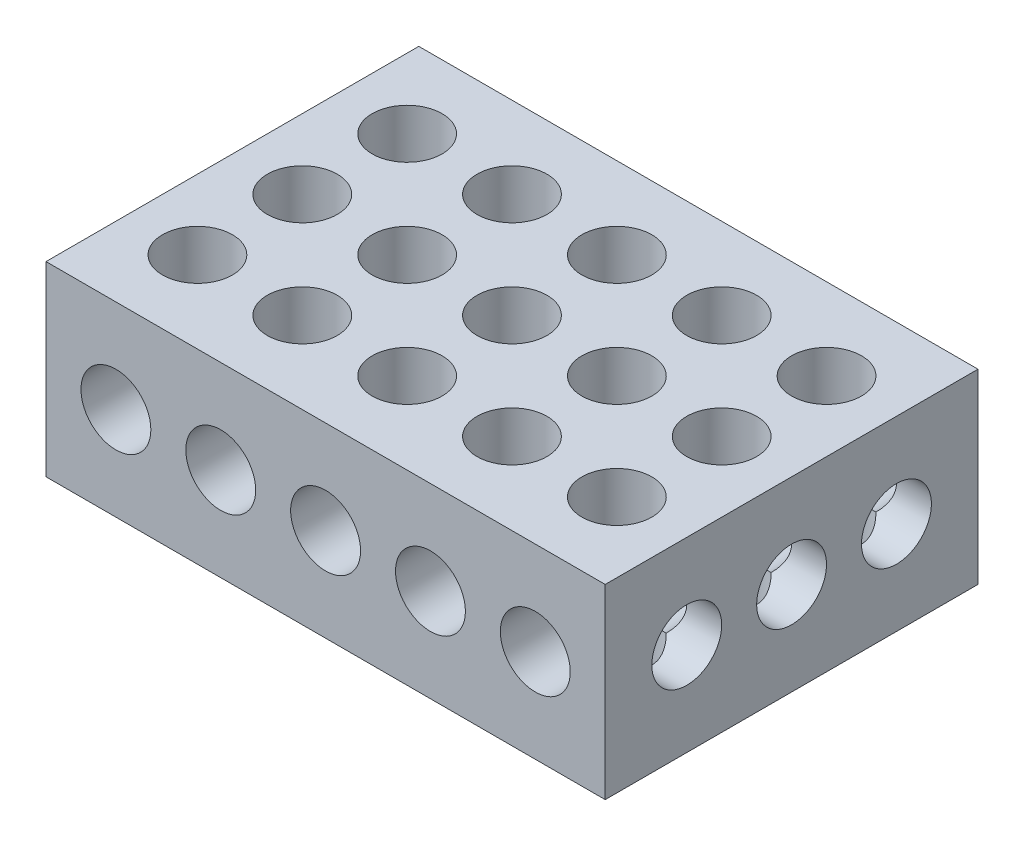
SolidWorks part; units mm, degrees
material "Plain Carbon Steel"
ref_plane "Front Plane" through (0, 0, 0) normal (0, 0, 1) x (1, 0, 0)
ref_plane "Top Plane" through (0, 0, 0) normal (0, 1, 0) x (1, 0, 0)
ref_plane "Right Plane" through (0, 0, 0) normal (1, 0, 0) x (0, 0, -1)
sketch "Sketch1" plane through (0, 0, 0) normal (0, 1, 0) x (1, 0, 0)
  line L1 (38.1, -25.4) -> (-38.1, -25.4)
  line L2 (38.1, -25.4) -> (38.1, 25.4)
  line L3 (38.1, 25.4) -> (-38.1, 25.4)
  line L4 (-38.1, -25.4) -> (-38.1, 25.4)
  line L5 (38.1, -25.4) -> (-38.1, 25.4) construction
  line L6 (38.1, 25.4) -> (-38.1, -25.4) construction
  point P0 (0, 0)
  dimension "D1" = 50.8
  dimension "D2" = 76.2
extrude "Boss-Extrude1" add sketch "Sketch1" along normal mid plane 25.4
sketch "Sketch2" plane through (0, 0, 25.4) normal (0, 0, 1) x (1, 0, 0)
  circle A0 centre (-28.575, 0) radius 4.7625
  circle A1 centre (-14.2875, 0) radius 4.7625
  circle A2 centre (0, 0) radius 4.7625
  circle A3 centre (14.2875, 0) radius 4.7625
  circle A4 centre (28.575, 0) radius 4.7625
  dimension "D1" = 9.525
  dimension "D3" = 14.2875
  dimension "D2" = 5
extrude "Cut-Extrude1" cut sketch "Sketch2" against normal through all
sketch "Sketch3" plane through (-38.1, 0, 0) normal (-1, 0, 0) x (0, 0, 1)
  circle A0 centre (-14.2875, 0) radius 4.7625
  circle A1 centre (0, 0) radius 4.7625
  circle A2 centre (14.2875, 0) radius 4.7625
  point P3 (0, 0)
  point P4 (-16.9977, 0)
  point P6 (14.2557, 0.9521)
  dimension "D1" = 3
  dimension "D3" = 9.525
  dimension "D2" = 14.2875
extrude "Cut-Extrude2" cut sketch "Sketch3" against normal through all
sketch "Sketch4" plane through (0, 12.7, 0) normal (0, 1, 0) x (1, 0, 0)
  circle A0 centre (-28.575, 14.2875) radius 4.7625
  circle A1 centre (-14.2875, 14.2875) radius 4.7625
  circle A2 centre (0, 14.2875) radius 4.7625
  circle A3 centre (14.2875, 14.2875) radius 4.7625
  circle A4 centre (28.575, 14.2875) radius 4.7625
  circle A5 centre (-14.2875, 0) radius 4.7625
  circle A6 centre (0, 0) radius 4.7625
  circle A7 centre (14.2875, 0) radius 4.7625
  circle A8 centre (28.575, 0) radius 4.7625
  circle A9 centre (-14.2875, -14.2875) radius 4.7625
  circle A10 centre (0, -14.2875) radius 4.7625
  circle A11 centre (14.2875, -14.2875) radius 4.7625
  circle A12 centre (28.575, -14.2875) radius 4.7625
  circle A13 centre (-28.575, 0) radius 4.7625
  circle A14 centre (-28.575, -14.2875) radius 4.7625
  point P2 (30.7663, 1.2012)
  point P3 (0, 0)
  point P33 (14.2231, 15.6426)
  point P34 (8.1162, 12.886)
  dimension "D1" = 5
  dimension "D5" = 9.525
  dimension "D3" = 14.2875
  dimension "D4" = 14.2875
  dimension "D2" = 3
extrude "Cut-Extrude3" cut sketch "Sketch4" against normal through all
